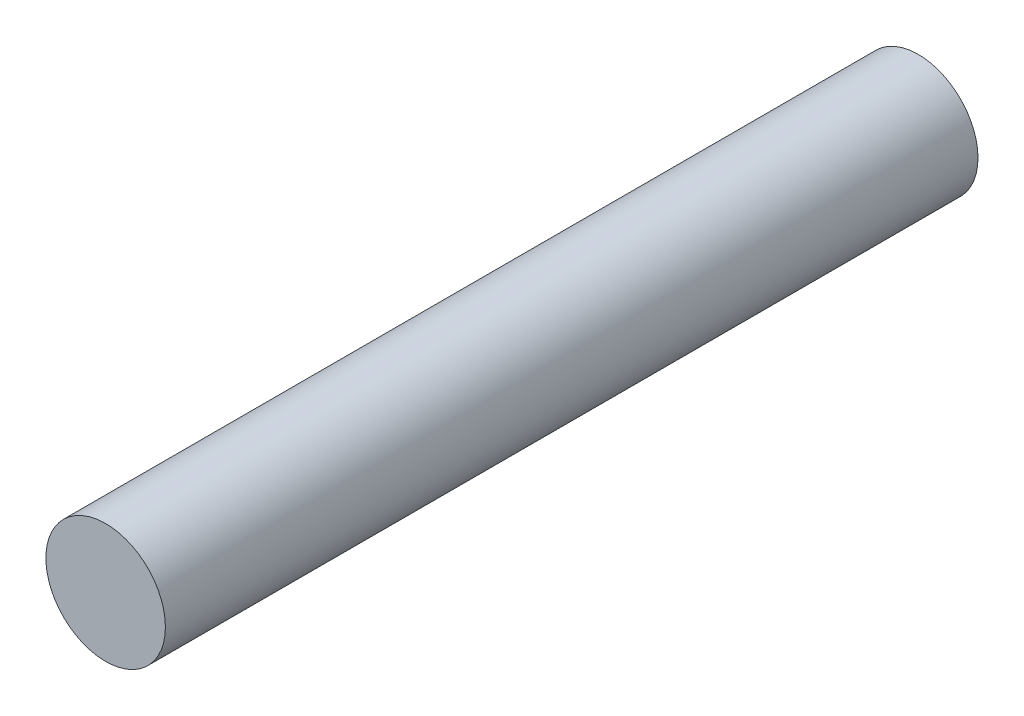
SolidWorks part; units mm, degrees
ref_plane "Front Plane" through (0, 0, 0) normal (0, 0, 1) x (1, 0, 0)
ref_plane "Top Plane" through (0, 0, 0) normal (0, 1, 0) x (1, 0, 0)
ref_plane "Right Plane" through (0, 0, 0) normal (1, 0, 0) x (0, 0, -1)
sketch "Sketch1" plane through (0, 0, 0) normal (0, 0, 1) x (1, 0, 0)
  circle A0 centre (-40.9832, 47.5012) radius 2.5
extrude "Boss-Extrude1" add sketch "Sketch1" along normal blind 34
